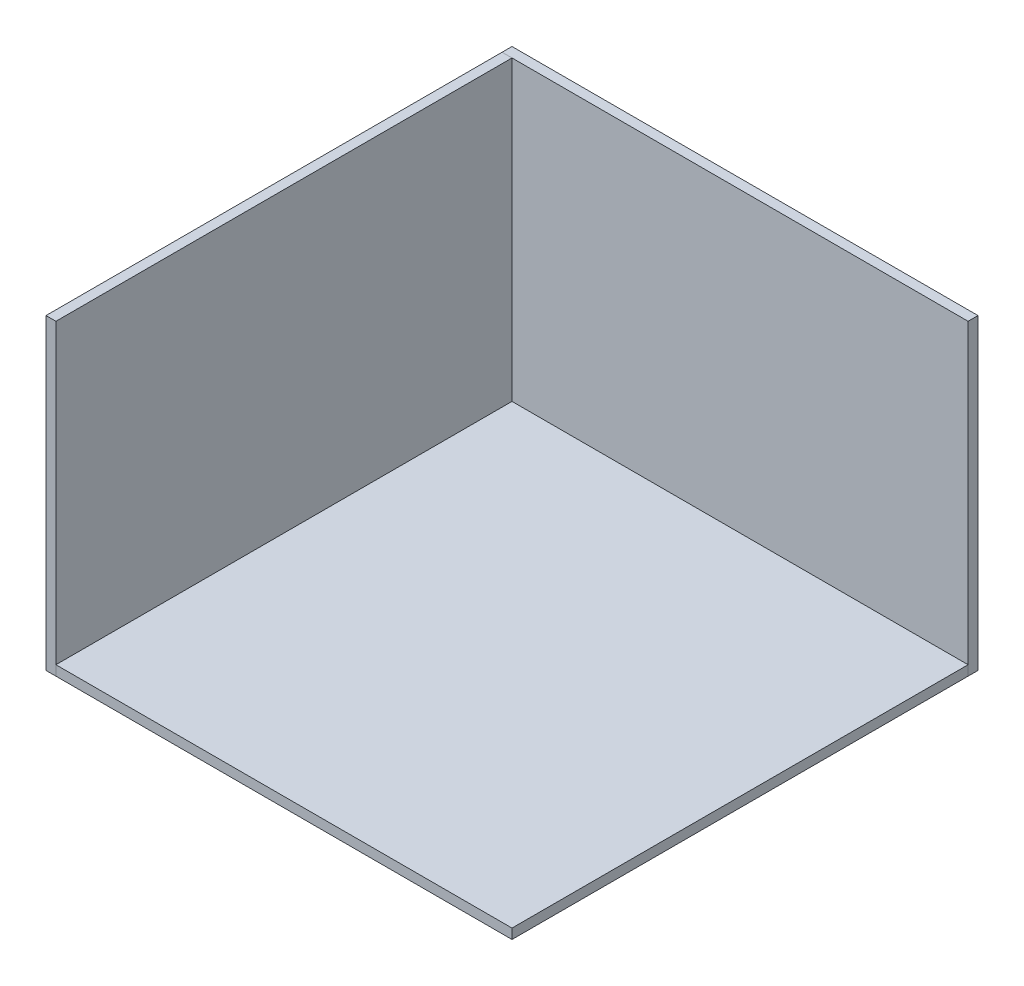
SolidWorks part; units mm, degrees
ref_plane "Front Plane" through (0, 0, 0) normal (0, 0, 1) x (1, 0, 0)
ref_plane "Top Plane" through (0, 0, 0) normal (0, 1, 0) x (1, 0, 0)
ref_plane "Right Plane" through (0, 0, 0) normal (1, 0, 0) x (0, 0, -1)
sketch "Sketch1" plane through (0, 0, 0) normal (0, 1, 0) x (1, 0, 0)
  line L1 (0, 0) -> (2300, 0)
  line L2 (0, 0) -> (0, -2300)
  line L3 (0, -2300) -> (2300, -2300)
  line L4 (2300, 0) -> (2300, -2300)
  dimension "D1" = 2300
extrude "Boss-Extrude1" add sketch "Sketch1" against normal blind 50
sketch "Sketch2" plane through (0, -50, 0) normal (0, -1, 0) x (1, 0, 0)
  line L0 (0, 0) -> (2300, 0)
  line L1 (2300, 0) -> (2300, -50)
  line L2 (2300, -50) -> (-50, -50)
  line L3 (-50, -50) -> (-50, 0)
  line L4 (-50, 0) -> (0, 0)
  line L6 (0, 0) -> (0, 2300) construction
extrude "Boss-Extrude2" add sketch "Sketch2" against normal blind 1550 separate body
sketch "Sketch3" plane through (0, -50, 0) normal (0, -1, 0) x (1, 0, 0)
  line L1 (-50, 0) -> (0, 0)
  line L2 (-50, 0) -> (-50, 2300)
  line L3 (-50, 2300) -> (0, 2300)
  line L4 (0, 0) -> (0, 2300)
extrude "Boss-Extrude3" add sketch "Sketch3" against normal blind 1550 separate body
